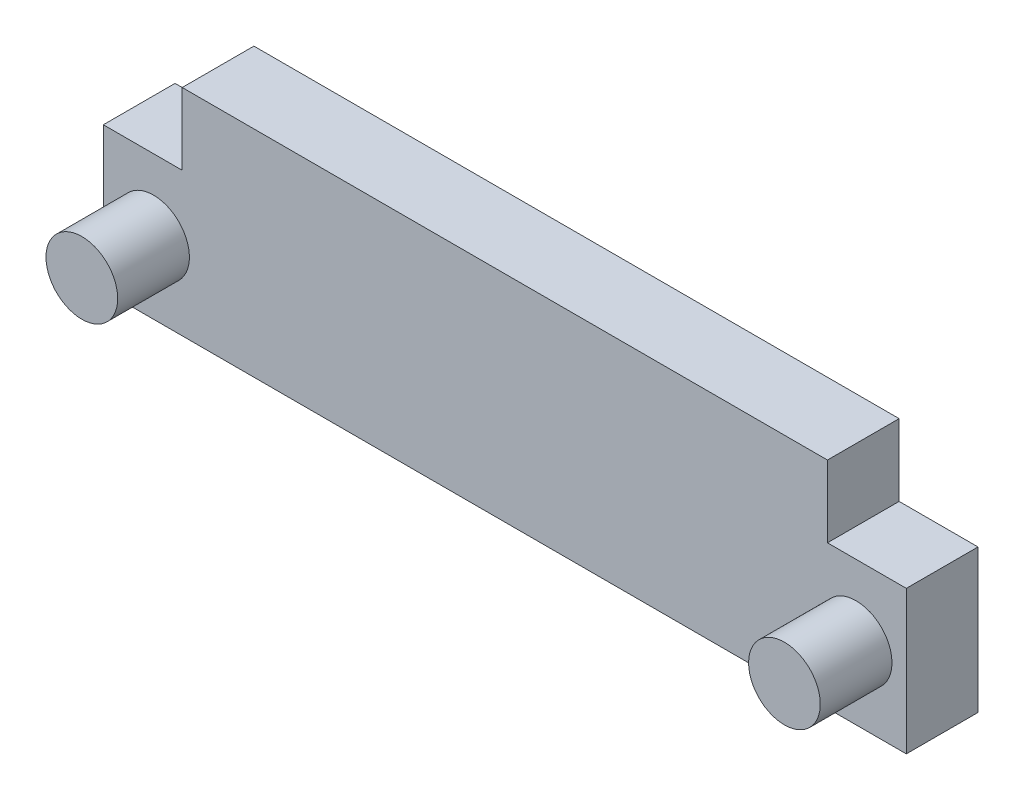
SolidWorks part; units mm, degrees
ref_plane "Front Plane" through (0, 0, 0) normal (0, 0, 1) x (1, 0, 0)
ref_plane "Top Plane" through (0, 0, 0) normal (0, 1, 0) x (1, 0, 0)
ref_plane "Right Plane" through (0, 0, 0) normal (1, 0, 0) x (0, 0, -1)
sketch "Sketch1" plane through (0, 0, 0) normal (0, 0, 1) x (1, 0, 0)
  line L1 (-45, -15) -> (45, -15)
  line L2 (-45, -15) -> (-45, 15)
  line L3 (-45, 15) -> (45, 15)
  line L4 (45, -15) -> (45, 15)
  line L5 (-45, -15) -> (45, 15) construction
  line L6 (-45, 15) -> (45, -15) construction
  point P0 (0, 0)
  dimension "D1" = 30
  dimension "D2" = 90
extrude "Boss-Extrude1" add sketch "Sketch1" along normal blind 10
sketch "Sketch3" plane through (45, 0, 0) normal (1, 0, 0) x (0, 0, -1)
  line L5 (-10, -15) -> (0, -15) construction
  line L6 (-10, -15) -> (0, -15)
  line L7 (-10, -15) -> (-10, 5)
  line L8 (-10, 5) -> (0, 5)
  line L9 (0, -15) -> (0, 5)
  line L10 (0, -15) -> (0, 15) construction
  dimension "D1" = 20
  dimension "D2" = 0
extrude "Boss-Extrude2" add sketch "Sketch3" along normal blind 11
ref_plane "Plane1" through (0, 0, 0) normal (1, 0, 0) x (0, 0, -1)
mirror "Mirror1" about plane through (0, 0, 0) normal (1, 0, 0) of "Boss-Extrude2"
sketch "Sketch4" plane through (0, 0, 10) normal (0, 0, 1) x (1, 0, 0)
  line L0 (-56, 5) -> (-45, 5) construction
  line L1 (-56, 5) -> (-56, -15) construction
  circle A0 centre (-49, -5) radius 5
  dimension "D1" = 10
  dimension "D2" = 10
  dimension "D3" = 7
extrude "Boss-Extrude3" add sketch "Sketch4" along normal blind 10
mirror "Mirror2" about plane through (0, 0, 0) normal (1, 0, 0) of "Boss-Extrude3"
